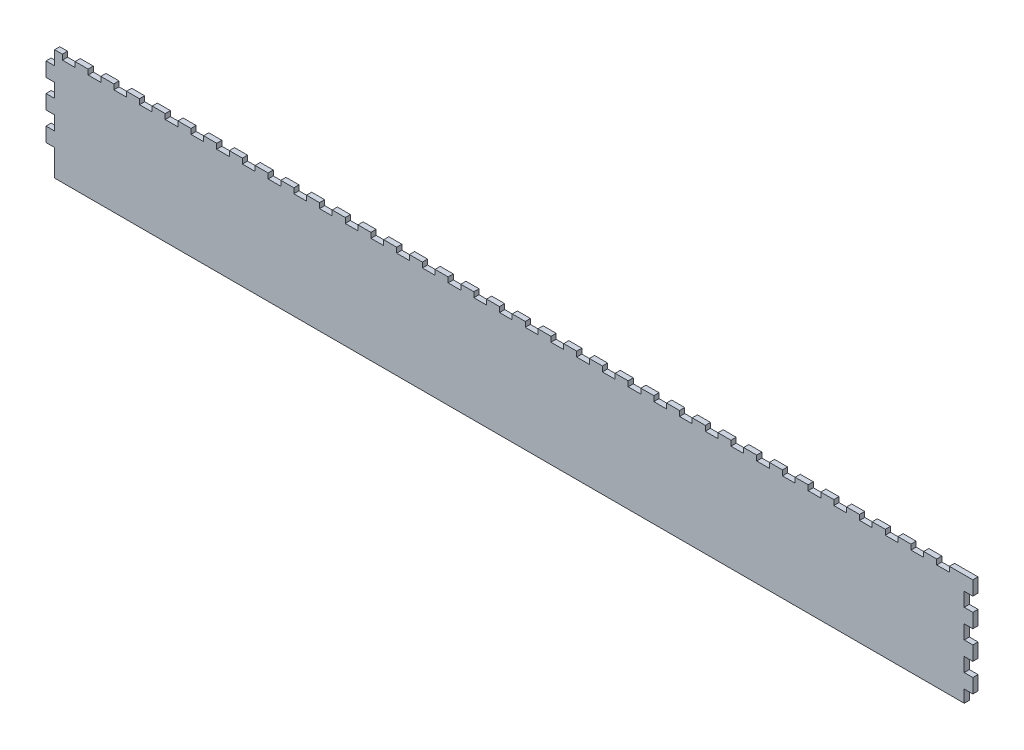
SolidWorks part; units mm, degrees
material "Perspex (TM) GS Acrylic Cast Sheet"
ref_plane "Front Plane" through (0, 0, 0) normal (0, 0, 1) x (1, 0, 0)
ref_plane "Top Plane" through (0, 0, 0) normal (0, 1, 0) x (1, 0, 0)
ref_plane "Right Plane" through (0, 0, 0) normal (1, 0, 0) x (0, 0, -1)
sketch "Sketch1" plane through (0, 0, 0) normal (0, 0, 1) x (1, 0, 0)
  line L0 (4.9997, 15.394) -> (4.9997, 0)
  line L1 (538.2002, 64.5533) -> (538.2002, -2.9072) construction
  line L1158 (538.3599, 64.6) -> (524.7414, 64.6)
  line L1159 (524.7414, 61.6) -> (524.7414, 64.6)
  line L1160 (524.7414, 61.6) -> (517.3729, 61.6)
  line L1161 (517.3729, 61.6) -> (517.3729, 64.6)
  line L1162 (517.3729, 64.6) -> (509.8045, 64.6)
  line L1163 (509.8045, 61.6) -> (509.8045, 64.6)
  line L1164 (509.8045, 61.6) -> (502.436, 61.6)
  line L1165 (502.436, 61.6) -> (502.436, 64.6)
  line L1166 (502.436, 64.6) -> (494.8676, 64.6)
  line L1167 (494.8676, 61.6) -> (494.8676, 64.6)
  line L1168 (494.8676, 61.6) -> (487.4991, 61.6)
  line L1169 (487.4991, 61.6) -> (487.4991, 64.6)
  line L1170 (487.4991, 64.6) -> (479.9307, 64.6)
  line L1171 (479.9307, 61.6) -> (479.9307, 64.6)
  line L1172 (479.9307, 61.6) -> (472.5622, 61.6)
  line L1173 (472.5622, 61.6) -> (472.5622, 64.6)
  line L1174 (472.5622, 64.6) -> (464.9938, 64.6)
  line L1175 (464.9938, 61.6) -> (464.9938, 64.6)
  line L1176 (464.9938, 61.6) -> (457.6253, 61.6)
  line L1177 (457.6253, 61.6) -> (457.6253, 64.6)
  line L1178 (457.6253, 64.6) -> (450.0567, 64.6)
  line L1179 (450.0567, 61.6) -> (450.0567, 64.6)
  line L1180 (450.0567, 61.6) -> (442.6886, 61.6)
  line L1181 (442.6886, 61.6) -> (442.6886, 64.6)
  line L1182 (442.6886, 64.6) -> (435.1201, 64.6)
  line L1183 (435.1201, 61.6) -> (435.1201, 64.6)
  line L1184 (435.1201, 61.6) -> (427.7516, 61.6)
  line L1185 (427.7516, 61.6) -> (427.7516, 64.6)
  line L1186 (427.7516, 64.6) -> (420.1831, 64.6)
  line L1187 (420.1831, 61.6) -> (420.1831, 64.6)
  line L1188 (420.1831, 61.6) -> (412.8147, 61.6)
  line L1189 (412.8147, 61.6) -> (412.8147, 64.6)
  line L1190 (412.8147, 64.6) -> (405.2462, 64.6)
  line L1191 (405.2462, 61.6) -> (405.2462, 64.6)
  line L1192 (405.2462, 61.6) -> (397.8777, 61.6)
  line L1193 (397.8777, 61.6) -> (397.8777, 64.6)
  line L1194 (397.8777, 64.6) -> (390.3092, 64.6)
  line L1195 (390.3092, 61.6) -> (390.3092, 64.6)
  line L1196 (390.3092, 61.6) -> (382.9407, 61.6)
  line L1197 (382.9407, 61.6) -> (382.9407, 64.6)
  line L1198 (382.9407, 64.6) -> (375.3722, 64.6)
  line L1199 (375.3722, 61.6) -> (375.3722, 64.6)
  line L1200 (375.3722, 61.6) -> (368.0038, 61.6)
  line L1201 (368.0038, 61.6) -> (368.0038, 64.6)
  line L1202 (368.0038, 64.6) -> (360.4356, 64.6)
  line L1203 (360.4356, 61.6) -> (360.4356, 64.6)
  line L1204 (360.4356, 61.6) -> (353.0672, 61.6)
  line L1205 (353.0672, 61.6) -> (353.0672, 64.6)
  line L1206 (353.0672, 64.6) -> (345.4986, 64.6)
  line L1207 (345.4986, 61.6) -> (345.4986, 64.6)
  line L1208 (345.4986, 61.6) -> (338.1302, 61.6)
  line L1209 (338.1302, 61.6) -> (338.1302, 64.6)
  line L1210 (338.1302, 64.6) -> (330.5617, 64.6)
  line L1211 (330.5617, 61.6) -> (330.5617, 64.6)
  line L1212 (330.5617, 61.6) -> (323.1932, 61.6)
  line L1213 (323.1932, 61.6) -> (323.1932, 64.6)
  line L1214 (323.1932, 64.6) -> (315.6247, 64.6)
  line L1215 (315.6247, 61.6) -> (315.6247, 64.6)
  line L1216 (315.6247, 61.6) -> (308.2563, 61.6)
  line L1217 (308.2563, 61.6) -> (308.2563, 64.6)
  line L1218 (308.2563, 64.6) -> (300.6878, 64.6)
  line L1219 (300.6878, 61.6) -> (300.6878, 64.6)
  line L1220 (300.6878, 61.6) -> (293.3193, 61.6)
  line L1221 (293.3193, 61.6) -> (293.3193, 64.6)
  line L1222 (293.3193, 64.6) -> (285.7508, 64.6)
  line L1223 (285.7508, 61.6) -> (285.7508, 64.6)
  line L1224 (285.7508, 61.6) -> (278.3823, 61.6)
  line L1225 (278.3823, 61.6) -> (278.3823, 64.6)
  line L1226 (278.3823, 64.6) -> (270.8142, 64.6)
  line L1227 (270.8142, 61.6) -> (270.8142, 64.6)
  line L1228 (270.8142, 61.6) -> (263.4457, 61.6)
  line L1229 (263.4457, 61.6) -> (263.4457, 64.6)
  line L1230 (263.4457, 64.6) -> (255.8772, 64.6)
  line L1231 (255.8772, 61.6) -> (255.8772, 64.6)
  line L1232 (255.8772, 61.6) -> (248.5088, 61.6)
  line L1233 (248.5088, 61.6) -> (248.5087, 64.6)
  line L1234 (248.5087, 64.6) -> (240.9403, 64.6)
  line L1235 (240.9403, 61.6) -> (240.9403, 64.6)
  line L1236 (240.9403, 61.6) -> (233.5718, 61.6)
  line L1237 (233.5718, 61.6) -> (233.5718, 64.6)
  line L1238 (233.5718, 64.6) -> (226.0033, 64.6)
  line L1239 (226.0033, 61.6) -> (226.0033, 64.6)
  line L1240 (226.0033, 61.6) -> (218.6348, 61.6)
  line L1241 (218.6348, 61.6) -> (218.6348, 64.6)
  line L1242 (218.6348, 64.6) -> (211.0664, 64.6)
  line L1243 (211.0664, 61.6) -> (211.0664, 64.6)
  line L1244 (211.0664, 61.6) -> (203.6979, 61.6)
  line L1245 (203.6979, 61.6) -> (203.6979, 64.6)
  line L1246 (203.6979, 64.6) -> (196.1297, 64.6)
  line L1247 (196.1297, 61.6) -> (196.1297, 64.6)
  line L1248 (196.1297, 61.6) -> (188.7613, 61.6)
  line L1249 (188.7613, 61.6) -> (188.7613, 64.6)
  line L1250 (188.7613, 64.6) -> (181.1928, 64.6)
  line L1251 (181.1928, 61.6) -> (181.1928, 64.6)
  line L1252 (181.1928, 61.6) -> (173.8243, 61.6)
  line L1253 (173.8243, 61.6) -> (173.8243, 64.6)
  line L1254 (173.8243, 64.6) -> (166.2558, 64.6)
  line L1255 (166.2558, 61.6) -> (166.2558, 64.6)
  line L1256 (166.2558, 61.6) -> (158.8873, 61.6)
  line L1257 (158.8873, 61.6) -> (158.8873, 64.6)
  line L1258 (158.8873, 64.6) -> (151.3188, 64.6)
  line L1259 (151.3188, 61.6) -> (151.3188, 64.6)
  line L1260 (151.3188, 61.6) -> (143.9504, 61.6)
  line L1261 (143.9504, 61.6) -> (143.9504, 64.6)
  line L1262 (143.9504, 64.6) -> (136.3819, 64.6)
  line L1263 (136.3819, 61.6) -> (136.3819, 64.6)
  line L1264 (136.3819, 61.6) -> (129.0134, 61.6)
  line L1265 (129.0134, 61.6) -> (129.0134, 64.6)
  line L1266 (129.0134, 64.6) -> (121.4449, 64.6)
  line L1267 (121.4449, 61.6) -> (121.4449, 64.6)
  line L1268 (121.4449, 61.6) -> (114.0764, 61.6)
  line L1269 (114.0764, 61.6) -> (114.0764, 64.6)
  line L1270 (114.0764, 64.6) -> (106.5083, 64.6)
  line L1271 (106.5083, 61.6) -> (106.5083, 64.6)
  line L1272 (106.5083, 61.6) -> (99.1398, 61.6)
  line L1273 (99.1398, 61.6) -> (99.1398, 64.6)
  line L1274 (99.1398, 64.6) -> (91.5713, 64.6)
  line L1275 (91.5713, 61.6) -> (91.5713, 64.6)
  line L1276 (91.5713, 61.6) -> (84.2029, 61.6)
  line L1277 (84.2029, 61.6) -> (84.2029, 64.6)
  line L1278 (84.2029, 64.6) -> (76.6344, 64.6)
  line L1279 (76.6344, 61.6) -> (76.6344, 64.6)
  line L1280 (76.6344, 61.6) -> (69.2659, 61.6)
  line L1281 (69.2659, 61.6) -> (69.2659, 64.6)
  line L1282 (69.2659, 64.6) -> (61.6974, 64.6)
  line L1283 (61.6974, 61.6) -> (61.6974, 64.6)
  line L1284 (61.6974, 61.6) -> (54.3289, 61.6)
  line L1285 (54.3289, 61.6) -> (54.3289, 64.6)
  line L1286 (54.3289, 64.6) -> (46.7604, 64.6)
  line L1287 (46.7604, 61.6) -> (46.7604, 64.6)
  line L1288 (46.7604, 61.6) -> (39.392, 61.6)
  line L1289 (39.392, 61.6) -> (39.392, 64.6)
  line L1290 (39.392, 64.6) -> (31.8235, 64.6)
  line L1291 (31.8235, 61.6) -> (31.8235, 64.6)
  line L1292 (31.8235, 61.6) -> (24.4554, 61.6)
  line L1293 (24.4554, 61.6) -> (24.4554, 64.6)
  line L1294 (24.4554, 64.6) -> (16.8869, 64.6)
  line L1295 (16.8869, 61.6) -> (16.8869, 64.6)
  line L1296 (16.8869, 61.6) -> (9.5184, 61.6)
  line L1297 (9.5184, 61.6) -> (9.5184, 64.6)
  line L1298 (9.5184, 64.6) -> (4.9997, 64.6)
  line L1299 (538.3599, 64.6) -> (538.3599, 56.3612)
  line L1300 (533.3598, 56.3612) -> (538.3599, 56.3612)
  line L1301 (533.3598, 56.3612) -> (533.3598, 48.2612)
  line L1302 (533.3598, 48.2612) -> (538.3599, 48.2612)
  line L1303 (538.3599, 48.2612) -> (538.3599, 39.9612)
  line L1304 (533.3598, 39.9612) -> (538.3599, 39.9612)
  line L1305 (533.3598, 39.9612) -> (533.3598, 31.8612)
  line L1306 (533.3598, 31.8612) -> (538.3599, 31.8612)
  line L1307 (538.3599, 31.8612) -> (538.3599, 23.5612)
  line L1308 (4.9997, 64.6) -> (4.9997, 56.4542)
  line L1309 (0, 56.4542) -> (4.9997, 56.4542)
  line L1310 (0, 56.4542) -> (0, 48.1649)
  line L1311 (0, 48.1649) -> (4.9997, 48.1649)
  line L1312 (4.9997, 48.1649) -> (4.9997, 40.0757)
  line L1313 (0, 40.0757) -> (4.9997, 40.0757)
  line L1314 (0, 40.0757) -> (0, 31.7864)
  line L1315 (0, 31.7864) -> (4.9997, 31.7864)
  line L1316 (4.9997, 31.7864) -> (4.9997, 23.6833)
  line L1317 (4.9997, 0) -> (533.3598, 0)
  line L1318 (533.3598, 23.5612) -> (538.3599, 23.5612)
  line L1319 (533.3598, 23.5612) -> (533.3598, 15.4612)
  line L1320 (533.3598, 15.4612) -> (538.3599, 15.4612)
  line L1321 (538.3599, 15.4612) -> (538.3599, 7.1612)
  line L1322 (533.3598, 7.1612) -> (538.3599, 7.1612)
  line L1323 (533.3598, 7.1612) -> (533.3598, 0)
  line L1324 (0, 23.6833) -> (4.9997, 23.6833)
  line L1325 (0, 23.6833) -> (0, 15.394)
  line L1326 (0, 15.394) -> (4.9997, 15.394)
  dimension "D1" = 64.6
  dimension "D2" = 64.6
  dimension "D4" = 8.1
  dimension "D5" = 8.3
  dimension "D6" = 8.3
  dimension "D7" = 8.3
extrude "Boss-Extrude1" add sketch "Sketch1" along normal blind 3
sketch "Sketch3" plane through (0, 0, 3) normal (0, 0, 1) x (1, 0, 0)
  line L0 (388.1696, 22.6554) -> (388.1696, 19.4364)
  line L1 (390.0144, 23.5966) -> (388.1696, 22.6554)
  line L2 (391.8592, 24.5377) -> (390.0144, 23.5966)
  line L3 (391.8592, 20.3776) -> (391.8592, 24.5377)
  line L4 (391.8592, 16.2174) -> (391.8592, 20.3776)
  line L5 (390.0144, 16.2174) -> (391.8592, 16.2174)
  line L6 (388.1696, 16.2174) -> (390.0144, 16.2174)
  line L7 (388.1696, 19.4364) -> (388.1696, 16.2174)
  line L8 (393.704, 27.2964) -> (393.704, 20.8345)
  line L9 (390.0144, 25.4413) -> (393.704, 27.2964)
  line L10 (386.3248, 23.5862) -> (390.0144, 25.4413)
  line L11 (386.3248, 18.9794) -> (386.3248, 23.5862)
  line L12 (386.3248, 14.3726) -> (386.3248, 18.9794)
  line L13 (390.0144, 14.3726) -> (386.3248, 14.3726)
  line L14 (393.704, 14.3726) -> (390.0144, 14.3726)
  line L15 (393.704, 20.8345) -> (393.704, 14.3726)
  line L16 (434.7504, 28.1897) -> (434.7504, 22.2036)
  line L17 (436.5952, 29.1309) -> (434.7504, 28.1897)
  line L18 (438.44, 30.072) -> (436.5952, 29.1309)
  line L19 (438.44, 23.1447) -> (438.44, 30.072)
  line L20 (438.44, 16.2174) -> (438.44, 23.1447)
  line L21 (436.5952, 16.2174) -> (438.44, 16.2174)
  line L22 (434.7504, 16.2174) -> (436.5952, 16.2174)
  line L23 (434.7504, 22.2036) -> (434.7504, 16.2174)
  line L24 (432.9056, 29.0475) -> (436.3429, 30.934)
  line L25 (432.9056, 21.7101) -> (432.9056, 29.0475)
  line L26 (432.9056, 14.3726) -> (432.9056, 21.7101)
  line L27 (436.5952, 14.3726) -> (432.9056, 14.3726)
  line L28 (440.2848, 14.3726) -> (436.5952, 14.3726)
  line L29 (440.2848, 23.5966) -> (440.2848, 14.3726)
  line L30 (146.503, 36.9712) -> (146.503, 26.5943)
  line L31 (148.3478, 36.9712) -> (146.503, 36.9712)
  line L32 (150.1926, 36.9712) -> (148.3478, 36.9712)
  line L33 (150.1926, 26.5943) -> (150.1926, 36.9712)
  line L34 (150.1926, 16.2174) -> (150.1926, 26.5943)
  line L35 (148.3478, 16.2174) -> (150.1926, 16.2174)
  line L36 (146.503, 16.2174) -> (148.3478, 16.2174)
  line L37 (146.503, 26.5943) -> (146.503, 16.2174)
  line L38 (152.0374, 38.816) -> (152.0374, 26.5943)
  line L39 (148.3478, 38.816) -> (152.0374, 38.816)
  line L40 (144.6582, 38.816) -> (148.3478, 38.816)
  line L41 (144.6582, 26.5943) -> (144.6582, 38.816)
  line L42 (144.6582, 14.3726) -> (144.6582, 26.5943)
  line L43 (148.3478, 14.3726) -> (144.6582, 14.3726)
  line L44 (152.0374, 14.3726) -> (148.3478, 14.3726)
  line L45 (152.0374, 26.5943) -> (152.0374, 14.3726)
  line L46 (186.6271, 36.9712) -> (186.6271, 26.5943)
  line L47 (188.4718, 36.9712) -> (186.6271, 36.9712)
  line L48 (190.3166, 36.9712) -> (188.4718, 36.9712)
  line L49 (190.3166, 26.5943) -> (190.3166, 36.9712)
  line L50 (190.3166, 16.2174) -> (190.3166, 26.5943)
  line L51 (188.4718, 16.2174) -> (190.3166, 16.2174)
  line L52 (186.6271, 16.2174) -> (188.4718, 16.2174)
  line L53 (186.6271, 26.5943) -> (186.6271, 16.2174)
  line L54 (192.1614, 38.816) -> (192.1614, 26.5943)
  line L55 (188.4718, 38.816) -> (192.1614, 38.816)
  line L56 (184.7823, 38.816) -> (188.4718, 38.816)
  line L57 (184.7823, 26.5943) -> (184.7823, 38.816)
  line L58 (184.7823, 14.3726) -> (184.7823, 26.5943)
  line L59 (188.4718, 14.3726) -> (184.7823, 14.3726)
  line L60 (192.1614, 14.3726) -> (188.4718, 14.3726)
  line L61 (192.1614, 26.5943) -> (192.1614, 14.3726)
  line L62 (393.704, 38.816) -> (393.704, 35.1213)
  line L63 (390.0144, 38.816) -> (393.704, 38.816)
  line L64 (386.3248, 38.816) -> (390.0144, 38.816)
  line L65 (386.3248, 36.9764) -> (386.3248, 38.816)
  line L66 (393.704, 31.4266) -> (390.0144, 33.2817)
  line L67 (393.704, 35.1213) -> (393.704, 31.4266)
  line L68 (307.6212, 47.3012) -> (307.6214, 47.3012)
  line L69 (305.9931, 14.3726) -> (306.1502, 32.1059)
  line L70 (308.802, 14.3726) -> (305.9931, 14.3726)
  line L71 (311.611, 14.3726) -> (308.802, 14.3726)
  line L72 (311.611, 12.5279) -> (311.611, 14.3726)
  line L73 (311.611, 10.683) -> (311.611, 12.5279)
  line L74 (304.2319, 10.683) -> (311.611, 10.683)
  line L75 (296.8527, 10.683) -> (304.2319, 10.683)
  line L76 (296.8527, 12.5279) -> (296.8527, 10.683)
  line L77 (296.8527, 14.3726) -> (296.8527, 12.5279)
  line L78 (299.6653, 14.3726) -> (296.8527, 14.3726)
  line L79 (302.478, 14.3726) -> (299.6653, 14.3726)
  line L80 (302.3172, 32.1058) -> (302.478, 14.3726)
  line L81 (300.5424, 16.2174) -> (300.5455, 30.3992)
  line L82 (297.7752, 16.2174) -> (300.5424, 16.2174)
  line L83 (295.0081, 16.2174) -> (297.7752, 16.2174)
  line L84 (295.0081, 12.5279) -> (295.0081, 16.2174)
  line L85 (295.0081, 8.8383) -> (295.0081, 12.5279)
  line L86 (304.232, 8.8383) -> (295.0081, 8.8383)
  line L87 (313.4559, 8.8383) -> (304.232, 8.8383)
  line L88 (313.4559, 12.5279) -> (313.4559, 8.8383)
  line L89 (313.4559, 16.2174) -> (313.4559, 12.5279)
  line L90 (310.6887, 16.2174) -> (313.4559, 16.2174)
  line L91 (307.9215, 16.2174) -> (310.6887, 16.2174)
  line L92 (307.9215, 29.9837) -> (307.9215, 16.2174)
  line L93 (434.8264, 41.7178) -> (436.4182, 40.9587)
  line L94 (434.5024, 46.0388) -> (434.8264, 41.7178)
  line L95 (440.2848, 36.9084) -> (436.5956, 38.8999)
  line L96 (440.2848, 40.3292) -> (440.2848, 36.9084)
  line L97 (443.8891, 10.683) -> (444.0767, 29.938)
  line L98 (436.5526, 10.683) -> (443.8891, 10.683)
  line L99 (429.2161, 10.683) -> (436.5526, 10.683)
  line L100 (429.2161, 21.1916) -> (429.2161, 10.683)
  line L101 (429.2161, 31.7001) -> (429.2161, 21.1916)
  line L102 (432.2682, 33.2052) -> (429.2161, 31.7001)
  line L103 (429.4466, 38.1242) -> (432.0696, 36.7311)
  line L104 (429.108, 43.1974) -> (429.4466, 38.1242)
  line L105 (427.3713, 37.155) -> (427.4169, 41.7904)
  line L106 (429.5604, 36.0915) -> (427.3713, 37.155)
  line L107 (431.7495, 35.0279) -> (429.5604, 36.0915)
  line L108 (429.5604, 33.9153) -> (431.7495, 35.0279)
  line L109 (427.3713, 32.8028) -> (429.5604, 33.9153)
  line L110 (427.3713, 20.8205) -> (427.3713, 32.8028)
  line L111 (427.3713, 8.8383) -> (427.3713, 20.8205)
  line L112 (436.5952, 8.8383) -> (427.3713, 8.8383)
  line L113 (445.8191, 8.8383) -> (436.5952, 8.8383)
  line L115 (445.8191, 26.5247) -> (445.8191, 8.8383)
  line L116 (209.3814, 48.2705) -> (209.3813, 48.2705)
  line L117 (213.607, 33.0511) -> (213.8934, 39.969)
  line L118 (211.6626, 38.816) -> (213.607, 33.0511)
  line L119 (226.29, 8.8383) -> (226.3356, 28.0932)
  line L120 (229.9795, 8.8383) -> (226.29, 8.8383)
  line L121 (233.6691, 8.8383) -> (229.9795, 8.8383)
  line L122 (233.6691, 20.1376) -> (233.6691, 8.8383)
  line L123 (233.6691, 31.4369) -> (233.6691, 20.1376)
  line L124 (235.5139, 31.4369) -> (233.6691, 31.4369)
  line L125 (237.3587, 31.4369) -> (235.5139, 31.4369)
  line L126 (237.3587, 20.1376) -> (237.3587, 31.4369)
  line L127 (237.3587, 8.8383) -> (237.3587, 20.1376)
  line L128 (241.0482, 8.8383) -> (237.3587, 8.8383)
  line L129 (244.7378, 8.8383) -> (241.0482, 8.8383)
  line L130 (244.735, 26.2484) -> (244.7378, 8.8383)
  line L131 (242.814, 10.683) -> (243.0138, 29.7074)
  line L132 (241.0087, 10.683) -> (242.814, 10.683)
  line L133 (239.2034, 10.683) -> (241.0087, 10.683)
  line L134 (239.2034, 21.9824) -> (239.2034, 10.683)
  line L135 (239.2034, 33.2817) -> (239.2034, 21.9824)
  line L136 (235.5138, 33.2817) -> (239.2034, 33.2817)
  line L137 (231.8242, 33.2817) -> (235.5138, 33.2817)
  line L138 (231.8242, 21.9824) -> (231.8242, 33.2817)
  line L139 (231.8242, 10.683) -> (231.8242, 21.9824)
  line L140 (230.0246, 10.683) -> (231.8242, 10.683)
  line L141 (228.225, 10.683) -> (230.0246, 10.683)
  line L142 (228.0101, 30.3992) -> (228.225, 10.683)
  line L143 (115.6029, 25.9025) -> (115.6485, 37.5477)
  line L144 (119.2925, 25.9025) -> (115.6029, 25.9025)
  line L145 (122.982, 25.9025) -> (119.2925, 25.9025)
  line L146 (122.982, 31.4369) -> (122.982, 25.9025)
  line L147 (122.982, 36.9712) -> (122.982, 31.4369)
  line L148 (124.8268, 36.9712) -> (122.982, 36.9712)
  line L149 (126.6716, 36.9712) -> (124.8268, 36.9712)
  line L150 (126.6716, 26.5943) -> (126.6716, 36.9712)
  line L151 (126.6716, 16.2174) -> (126.6716, 26.5943)
  line L152 (124.8268, 16.2174) -> (126.6716, 16.2174)
  line L153 (122.982, 16.2174) -> (124.8268, 16.2174)
  line L154 (122.982, 18.9846) -> (122.982, 16.2174)
  line L155 (122.982, 21.7517) -> (122.982, 18.9846)
  line L156 (119.2925, 21.7517) -> (122.982, 21.7517)
  line L157 (115.6029, 21.7517) -> (119.2925, 21.7517)
  line L158 (115.6029, 15.295) -> (115.6029, 21.7517)
  line L159 (115.6029, 8.8383) -> (115.6029, 15.295)
  line L160 (124.8268, 8.8383) -> (115.6029, 8.8383)
  line L161 (134.0507, 8.8383) -> (124.8268, 8.8383)
  line L162 (134.0507, 26.0635) -> (134.0507, 8.8383)
  line L163 (132.1262, 10.683) -> (132.3074, 29.4768)
  line L164 (124.787, 10.683) -> (132.1262, 10.683)
  line L165 (117.4477, 10.683) -> (124.787, 10.683)
  line L166 (117.4477, 15.295) -> (117.4477, 10.683)
  line L167 (117.4477, 19.907) -> (117.4477, 15.295)
  line L168 (119.2925, 19.907) -> (117.4477, 19.907)
  line L169 (121.1373, 19.907) -> (119.2925, 19.907)
  line L170 (121.1373, 17.1398) -> (121.1373, 19.907)
  line L171 (121.1373, 14.3726) -> (121.1373, 17.1398)
  line L172 (124.8268, 14.3726) -> (121.1373, 14.3726)
  line L173 (128.5164, 14.3726) -> (124.8268, 14.3726)
  line L174 (128.5164, 26.5943) -> (128.5164, 14.3726)
  line L175 (128.5164, 38.816) -> (128.5164, 26.5943)
  line L176 (124.8268, 38.816) -> (128.5164, 38.816)
  line L177 (121.1373, 38.816) -> (124.8268, 38.816)
  line L178 (121.1373, 33.2817) -> (121.1373, 38.816)
  line L179 (121.1373, 27.7473) -> (121.1373, 33.2817)
  line L180 (119.3512, 27.7473) -> (121.1373, 27.7473)
  line L181 (117.565, 27.7473) -> (119.3512, 27.7473)
  line L182 (117.3014, 39.6231) -> (117.565, 27.7473)
  line L183 (173.8694, 51.0505) -> (173.8695, 51.0505)
  line L184 (172.2496, 10.683) -> (172.4314, 31.5522)
  line L185 (170.445, 10.683) -> (172.2496, 10.683)
  line L186 (168.6403, 10.683) -> (170.445, 10.683)
  line L187 (168.6403, 24.7495) -> (168.6403, 10.683)
  line L188 (168.6403, 38.816) -> (168.6403, 24.7495)
  line L189 (165.9388, 38.816) -> (168.6403, 38.816)
  line L190 (163.2372, 38.816) -> (165.9388, 38.816)
  line L191 (162.9119, 44.0045) -> (163.2372, 38.816)
  line L192 (161.2613, 36.9712) -> (161.2644, 40.3149)
  line L193 (164.0285, 36.9712) -> (161.2613, 36.9712)
  line L194 (166.7956, 36.9712) -> (164.0285, 36.9712)
  line L195 (166.7956, 22.9047) -> (166.7956, 36.9712)
  line L196 (166.7956, 8.8383) -> (166.7956, 22.9047)
  line L197 (170.4852, 8.8383) -> (166.7956, 8.8383)
  line L198 (174.1748, 8.8383) -> (170.4852, 8.8383)
  line L199 (174.1748, 28.1389) -> (174.1748, 8.8383)
  line L200 (249.3497, 31.4369) -> (249.3953, 40.5455)
  line L201 (253.0393, 31.4369) -> (249.3497, 31.4369)
  line L202 (256.7288, 31.4369) -> (253.0393, 31.4369)
  line L203 (256.7288, 34.204) -> (256.7288, 31.4369)
  line L204 (256.7288, 36.9712) -> (256.7288, 34.204)
  line L205 (258.5736, 36.9712) -> (256.7288, 36.9712)
  line L206 (260.4184, 36.9712) -> (258.5736, 36.9712)
  line L207 (260.4184, 26.5943) -> (260.4184, 36.9712)
  line L208 (260.4184, 16.2174) -> (260.4184, 26.5943)
  line L209 (258.5736, 16.2174) -> (260.4184, 16.2174)
  line L210 (256.7288, 16.2174) -> (258.5736, 16.2174)
  line L211 (256.7288, 18.9846) -> (256.7288, 16.2174)
  line L212 (256.7288, 21.7517) -> (256.7288, 18.9846)
  line L213 (253.0393, 21.7517) -> (256.7288, 21.7517)
  line L214 (249.3497, 21.7517) -> (253.0393, 21.7517)
  line L215 (249.3497, 15.295) -> (249.3497, 21.7517)
  line L216 (249.3497, 8.8383) -> (249.3497, 15.295)
  line L217 (258.5736, 8.8383) -> (249.3497, 8.8383)
  line L218 (267.7975, 8.8383) -> (258.5736, 8.8383)
  line L219 (267.7975, 26.2941) -> (267.7975, 8.8383)
  line L220 (265.8667, 10.683) -> (266.0553, 29.7074)
  line L221 (258.5306, 10.683) -> (265.8667, 10.683)
  line L222 (251.1945, 10.683) -> (258.5306, 10.683)
  line L223 (251.1945, 15.295) -> (251.1945, 10.683)
  line L224 (251.1945, 19.907) -> (251.1945, 15.295)
  line L225 (253.0393, 19.907) -> (251.1945, 19.907)
  line L226 (254.884, 19.907) -> (253.0393, 19.907)
  line L227 (254.884, 17.1398) -> (254.884, 19.907)
  line L228 (254.884, 14.3726) -> (254.884, 17.1398)
  line L229 (258.5736, 14.3726) -> (254.884, 14.3726)
  line L230 (262.2632, 14.3726) -> (258.5736, 14.3726)
  line L231 (262.2632, 26.5943) -> (262.2632, 14.3726)
  line L232 (262.2632, 38.816) -> (262.2632, 26.5943)
  line L233 (258.5736, 38.816) -> (262.2632, 38.816)
  line L234 (254.884, 38.816) -> (258.5736, 38.816)
  line L235 (254.884, 36.0488) -> (254.884, 38.816)
  line L236 (254.884, 33.2817) -> (254.884, 36.0488)
  line L237 (253.1053, 33.2817) -> (254.884, 33.2817)
  line L238 (251.3265, 33.2817) -> (253.1053, 33.2817)
  line L239 (251.0415, 42.6209) -> (251.3265, 33.2817)
  line L240 (352.3522, 51.0505) -> (352.3523, 51.0505)
  line L241 (350.7324, 10.683) -> (350.9142, 31.5522)
  line L242 (348.9277, 10.683) -> (350.7324, 10.683)
  line L243 (347.1231, 10.683) -> (348.9277, 10.683)
  line L244 (347.1231, 24.7495) -> (347.1231, 10.683)
  line L245 (347.1231, 38.816) -> (347.1231, 24.7495)
  line L246 (344.4215, 38.816) -> (347.1231, 38.816)
  line L247 (341.72, 38.816) -> (344.4215, 38.816)
  line L248 (341.3947, 44.0045) -> (341.72, 38.816)
  line L249 (339.7441, 36.9712) -> (339.7472, 40.3149)
  line L250 (342.5112, 36.9712) -> (339.7441, 36.9712)
  line L251 (345.2784, 36.9712) -> (342.5112, 36.9712)
  line L252 (345.2784, 22.9047) -> (345.2784, 36.9712)
  line L253 (345.2784, 8.8383) -> (345.2784, 22.9047)
  line L254 (348.968, 8.8383) -> (345.2784, 8.8383)
  line L255 (352.6576, 8.8383) -> (348.968, 8.8383)
  line L256 (352.6576, 28.1389) -> (352.6576, 8.8383)
  line L257 (397.3133, 10.683) -> (397.4951, 31.5522)
  line L258 (389.9743, 10.683) -> (397.3133, 10.683)
  line L259 (382.6353, 10.683) -> (389.9743, 10.683)
  line L260 (382.6353, 18.4244) -> (382.6353, 10.683)
  line L261 (382.6353, 26.1657) -> (382.6353, 18.4244)
  line L262 (385.6874, 27.6708) -> (382.6353, 26.1657)
  line L263 (382.8659, 32.5898) -> (385.4889, 31.1967)
  line L264 (382.5801, 40.208) -> (382.8659, 32.5898)
  line L265 (380.7905, 31.6207) -> (380.8361, 38.7926)
  line L266 (382.9665, 30.5635) -> (380.7905, 31.6207)
  line L267 (385.1425, 29.5063) -> (382.9665, 30.5635)
  line L268 (383.3124, 28.3986) -> (385.1425, 29.5063)
  line L269 (380.7905, 8.8383) -> (380.7905, 18.0622)
  line L270 (390.0144, 8.8383) -> (380.7905, 8.8383)
  line L271 (399.2383, 8.8383) -> (390.0144, 8.8383)
  line L272 (399.2383, 28.1389) -> (399.2383, 8.8383)
  line L273 (272.4095, 36.9712) -> (272.4551, 43.5433)
  line L274 (277.9438, 36.9712) -> (272.4095, 36.9712)
  line L275 (283.4782, 36.9712) -> (277.9438, 36.9712)
  line L276 (283.4782, 35.1264) -> (283.4782, 36.9712)
  line L277 (283.4782, 33.2817) -> (283.4782, 35.1264)
  line L278 (277.9438, 33.2817) -> (283.4782, 33.2817)
  line L279 (272.4095, 33.2817) -> (277.9438, 33.2817)
  line L280 (272.4095, 29.5921) -> (272.4095, 33.2817)
  line L281 (272.4095, 25.9025) -> (272.4095, 29.5921)
  line L282 (277.9438, 25.9025) -> (272.4095, 25.9025)
  line L283 (283.4782, 25.9025) -> (277.9438, 25.9025)
  line L284 (283.4782, 21.06) -> (283.4782, 25.9025)
  line L285 (283.4782, 16.2174) -> (283.4782, 21.06)
  line L286 (281.6334, 16.2174) -> (283.4782, 16.2174)
  line L287 (279.7886, 16.2174) -> (281.6334, 16.2174)
  line L288 (279.7886, 18.9846) -> (279.7886, 16.2174)
  line L289 (279.7886, 21.7517) -> (279.7886, 18.9846)
  line L290 (276.099, 21.7517) -> (279.7886, 21.7517)
  line L291 (272.4095, 21.7517) -> (276.099, 21.7517)
  line L292 (272.4095, 15.295) -> (272.4095, 21.7517)
  line L293 (272.4095, 8.8383) -> (272.4095, 15.295)
  line L294 (281.6334, 8.8383) -> (272.4095, 8.8383)
  line L295 (290.8573, 8.8383) -> (281.6334, 8.8383)
  line L296 (290.8573, 26.9859) -> (290.8573, 8.8383)
  line L297 (288.9288, 10.683) -> (289.1147, 30.3992)
  line L298 (281.5915, 10.683) -> (288.9288, 10.683)
  line L299 (274.2543, 10.683) -> (281.5915, 10.683)
  line L300 (274.2543, 15.295) -> (274.2543, 10.683)
  line L301 (274.2543, 19.907) -> (274.2543, 15.295)
  line L302 (276.099, 19.907) -> (274.2543, 19.907)
  line L303 (277.9438, 19.907) -> (276.099, 19.907)
  line L304 (277.9438, 17.1398) -> (277.9438, 19.907)
  line L305 (277.9438, 14.3726) -> (277.9438, 17.1398)
  line L306 (281.6334, 14.3726) -> (277.9438, 14.3726)
  line L307 (285.323, 14.3726) -> (281.6334, 14.3726)
  line L308 (285.323, 21.06) -> (285.323, 14.3726)
  line L309 (285.323, 27.7473) -> (285.323, 21.06)
  line L310 (279.7886, 27.7473) -> (285.323, 27.7473)
  line L311 (274.2543, 27.7473) -> (279.7886, 27.7473)
  line L312 (274.2543, 29.5921) -> (274.2543, 27.7473)
  line L313 (274.2543, 31.4369) -> (274.2543, 29.5921)
  line L314 (279.7886, 31.4369) -> (274.2543, 31.4369)
  line L315 (285.323, 31.4369) -> (279.7886, 31.4369)
  line L316 (285.323, 35.1264) -> (285.323, 31.4369)
  line L317 (285.323, 38.816) -> (285.323, 35.1264)
  line L318 (279.8603, 38.816) -> (285.323, 38.816)
  line L319 (274.3977, 38.816) -> (279.8603, 38.816)
  line L320 (274.0865, 45.6186) -> (274.3977, 38.816)
  line L321 (357.2695, 36.9712) -> (357.3151, 43.5433)
  line L322 (362.8039, 36.9712) -> (357.2695, 36.9712)
  line L323 (368.3382, 36.9712) -> (362.8039, 36.9712)
  line L324 (368.3382, 35.1264) -> (368.3382, 36.9712)
  line L325 (368.3382, 33.2817) -> (368.3382, 35.1264)
  line L326 (362.8039, 33.2817) -> (368.3382, 33.2817)
  line L327 (357.2695, 33.2817) -> (362.8039, 33.2817)
  line L328 (357.2695, 29.5921) -> (357.2695, 33.2817)
  line L329 (357.2695, 25.9025) -> (357.2695, 29.5921)
  line L330 (362.8039, 25.9025) -> (357.2695, 25.9025)
  line L331 (368.3382, 25.9025) -> (362.8039, 25.9025)
  line L332 (368.3382, 21.06) -> (368.3382, 25.9025)
  line L333 (368.3382, 16.2174) -> (368.3382, 21.06)
  line L334 (366.4934, 16.2174) -> (368.3382, 16.2174)
  line L335 (364.6486, 16.2174) -> (366.4934, 16.2174)
  line L336 (364.6486, 18.9846) -> (364.6486, 16.2174)
  line L337 (364.6486, 21.7517) -> (364.6486, 18.9846)
  line L338 (360.9591, 21.7517) -> (364.6486, 21.7517)
  line L339 (357.2695, 21.7517) -> (360.9591, 21.7517)
  line L340 (357.2695, 15.295) -> (357.2695, 21.7517)
  line L341 (357.2695, 8.8383) -> (357.2695, 15.295)
  line L342 (366.4934, 8.8383) -> (357.2695, 8.8383)
  line L343 (375.7173, 8.8383) -> (366.4934, 8.8383)
  line L344 (375.7173, 26.9859) -> (375.7173, 8.8383)
  line L345 (373.7888, 10.683) -> (373.9747, 30.3992)
  line L346 (366.4515, 10.683) -> (373.7888, 10.683)
  line L347 (359.1143, 10.683) -> (366.4515, 10.683)
  line L348 (359.1143, 15.295) -> (359.1143, 10.683)
  line L349 (359.1143, 19.907) -> (359.1143, 15.295)
  line L350 (360.9591, 19.907) -> (359.1143, 19.907)
  line L351 (362.8039, 19.907) -> (360.9591, 19.907)
  line L352 (362.8039, 17.1398) -> (362.8039, 19.907)
  line L353 (362.8039, 14.3726) -> (362.8039, 17.1398)
  line L354 (366.4934, 14.3726) -> (362.8039, 14.3726)
  line L355 (370.183, 14.3726) -> (366.4934, 14.3726)
  line L356 (370.183, 21.06) -> (370.183, 14.3726)
  line L357 (370.183, 27.7473) -> (370.183, 21.06)
  line L358 (364.6486, 27.7473) -> (370.183, 27.7473)
  line L359 (359.1143, 27.7473) -> (364.6486, 27.7473)
  line L360 (359.1143, 29.5921) -> (359.1143, 27.7473)
  line L361 (359.1143, 31.4369) -> (359.1143, 29.5921)
  line L362 (364.6486, 31.4369) -> (359.1143, 31.4369)
  line L363 (370.183, 31.4369) -> (364.6486, 31.4369)
  line L364 (370.183, 35.1264) -> (370.183, 31.4369)
  line L365 (370.183, 38.816) -> (370.183, 35.1264)
  line L366 (364.7204, 38.816) -> (370.183, 38.816)
  line L367 (359.2577, 38.816) -> (364.7204, 38.816)
  line L368 (358.9465, 45.6186) -> (359.2577, 38.816)
  line L369 (403.8503, 36.9712) -> (403.8959, 43.5433)
  line L370 (409.3846, 36.9712) -> (403.8503, 36.9712)
  line L371 (414.919, 36.9712) -> (409.3846, 36.9712)
  line L372 (414.919, 35.1264) -> (414.919, 36.9712)
  line L373 (414.919, 33.2817) -> (414.919, 35.1264)
  line L374 (409.3846, 33.2817) -> (414.919, 33.2817)
  line L375 (403.8503, 33.2817) -> (409.3846, 33.2817)
  line L376 (403.8503, 29.5921) -> (403.8503, 33.2817)
  line L377 (403.8503, 25.9025) -> (403.8503, 29.5921)
  line L378 (409.3846, 25.9025) -> (403.8503, 25.9025)
  line L379 (414.919, 25.9025) -> (409.3846, 25.9025)
  line L380 (414.919, 21.06) -> (414.919, 25.9025)
  line L381 (414.919, 16.2174) -> (414.919, 21.06)
  line L382 (413.0742, 16.2174) -> (414.919, 16.2174)
  line L383 (411.2294, 16.2174) -> (413.0742, 16.2174)
  line L384 (411.2294, 18.9846) -> (411.2294, 16.2174)
  line L385 (411.2294, 21.7517) -> (411.2294, 18.9846)
  line L386 (407.5398, 21.7517) -> (411.2294, 21.7517)
  line L387 (403.8503, 21.7517) -> (407.5398, 21.7517)
  line L388 (403.8503, 15.295) -> (403.8503, 21.7517)
  line L389 (403.8503, 8.8383) -> (403.8503, 15.295)
  line L390 (413.0742, 8.8383) -> (403.8503, 8.8383)
  line L391 (422.2981, 8.8383) -> (413.0742, 8.8383)
  line L393 (422.2981, 26.9859) -> (422.2981, 8.8383)
  line L394 (420.3695, 10.683) -> (420.5554, 30.3992)
  line L395 (413.0323, 10.683) -> (420.3695, 10.683)
  line L396 (405.6951, 10.683) -> (413.0323, 10.683)
  line L397 (405.6951, 15.295) -> (405.6951, 10.683)
  line L398 (405.6951, 19.907) -> (405.6951, 15.295)
  line L399 (407.5398, 19.907) -> (405.6951, 19.907)
  line L400 (409.3846, 19.907) -> (407.5398, 19.907)
  line L401 (409.3846, 17.1398) -> (409.3846, 19.907)
  line L402 (409.3846, 14.3726) -> (409.3846, 17.1398)
  line L403 (413.0742, 14.3726) -> (409.3846, 14.3726)
  line L404 (416.7638, 14.3726) -> (413.0742, 14.3726)
  line L405 (416.7638, 21.06) -> (416.7638, 14.3726)
  line L406 (416.7638, 27.7473) -> (416.7638, 21.06)
  line L407 (411.2294, 27.7473) -> (416.7638, 27.7473)
  line L408 (405.6951, 27.7473) -> (411.2294, 27.7473)
  line L409 (405.6951, 29.5921) -> (405.6951, 27.7473)
  line L410 (405.6951, 31.4369) -> (405.6951, 29.5921)
  line L411 (411.2294, 31.4369) -> (405.6951, 31.4369)
  line L412 (416.7638, 31.4369) -> (411.2294, 31.4369)
  line L413 (416.7638, 35.1264) -> (416.7638, 31.4369)
  line L414 (416.7638, 38.816) -> (416.7638, 35.1264)
  line L415 (411.3011, 38.816) -> (416.7638, 38.816)
  line L416 (405.8385, 38.816) -> (411.3011, 38.816)
  line L417 (405.5273, 45.6186) -> (405.8385, 38.816)
  line L418 (157.2664, 52.4341) -> (157.2665, 52.4341)
  line L419 (155.6485, 10.683) -> (155.828, 32.244)
  line L420 (148.3516, 10.683) -> (155.6485, 10.683)
  line L421 (141.0546, 10.683) -> (148.3516, 10.683)
  line L422 (140.866, 29.7074) -> (141.0546, 10.683)
  line L423 (139.1239, 8.8383) -> (139.127, 26.7096)
  line L424 (148.3478, 8.8383) -> (139.1239, 8.8383)
  line L425 (157.5717, 8.8383) -> (148.3478, 8.8383)
  line L426 (157.5717, 28.8307) -> (157.5717, 8.8383)
  line L427 (197.3904, 52.4341) -> (197.3905, 52.4341)
  line L428 (195.7726, 10.683) -> (195.9521, 32.244)
  line L429 (188.4756, 10.683) -> (195.7726, 10.683)
  line L430 (181.1786, 10.683) -> (188.4756, 10.683)
  line L431 (180.9901, 29.7074) -> (181.1786, 10.683)
  line L432 (179.2479, 8.8383) -> (179.251, 26.7096)
  line L433 (188.4718, 8.8383) -> (179.2479, 8.8383)
  line L434 (197.6958, 8.8383) -> (188.4718, 8.8383)
  line L435 (197.6958, 28.8307) -> (197.6958, 8.8383)
  line L436 (238.9031, 52.3743) -> (238.9032, 52.3743)
  line L437 (237.2189, 38.816) -> (237.4814, 46.9413)
  line L438 (235.5032, 38.816) -> (237.2189, 38.816)
  line L439 (233.7876, 38.816) -> (235.5032, 38.816)
  line L440 (233.4589, 43.8858) -> (233.7876, 38.816)
  line L441 (231.8242, 36.9712) -> (231.8274, 40.0843)
  line L442 (235.5138, 36.9712) -> (231.8242, 36.9712)
  line L443 (239.2034, 36.9712) -> (235.5138, 36.9712)
  line L444 (239.2034, 42.8972) -> (239.2034, 36.9712)
  line L445 (220.9063, 52.9282) -> (220.9065, 52.9282)
  line L446 (219.3002, 10.683) -> (219.4918, 32.244)
  line L447 (217.333, 10.683) -> (219.3002, 10.683)
  line L448 (215.3659, 10.683) -> (217.333, 10.683)
  line L449 (211.9498, 20.6957) -> (215.3659, 10.683)
  line L450 (208.5337, 30.7084) -> (211.9498, 20.6957)
  line L451 (208.4094, 20.6957) -> (208.5337, 30.7084)
  line L452 (208.2851, 10.683) -> (208.4094, 20.6957)
  line L453 (206.4912, 10.683) -> (208.2851, 10.683)
  line L454 (204.6973, 10.683) -> (206.4912, 10.683)
  line L455 (204.492, 30.3992) -> (204.6973, 10.683)
  line L456 (202.7689, 8.8383) -> (202.772, 27.632)
  line L457 (206.4585, 8.8383) -> (202.7689, 8.8383)
  line L458 (210.148, 8.8383) -> (206.4585, 8.8383)
  line L459 (210.1795, 14.4879) -> (210.148, 8.8383)
  line L460 (210.2109, 20.1376) -> (210.1795, 14.4879)
  line L461 (212.1395, 14.6032) -> (210.2109, 20.1376)
  line L462 (214.0682, 9.0689) -> (212.1395, 14.6032)
  line L463 (217.6425, 8.9342) -> (214.0682, 9.0689)
  line L464 (221.2167, 8.7995) -> (217.6425, 8.9342)
  line L465 (221.2167, 29.0419) -> (221.2167, 8.7995)
  line L466 (110.6808, 53.3894) -> (110.6806, 53.3894)
  line L467 (109.0112, 38.816) -> (109.2853, 46.541)
  line L468 (103.5444, 38.816) -> (109.0112, 38.816)
  line L469 (98.0776, 38.816) -> (103.5444, 38.816)
  line L470 (98.0776, 35.1264) -> (98.0776, 38.816)
  line L471 (98.0776, 31.4369) -> (98.0776, 35.1264)
  line L472 (103.612, 31.4369) -> (98.0776, 31.4369)
  line L473 (109.1463, 31.4369) -> (103.612, 31.4369)
  line L474 (109.1463, 21.06) -> (109.1463, 31.4369)
  line L475 (109.1463, 10.683) -> (109.1463, 21.06)
  line L476 (107.3016, 10.683) -> (109.1463, 10.683)
  line L477 (105.4568, 10.683) -> (107.3016, 10.683)
  line L478 (105.4568, 19.2152) -> (105.4568, 10.683)
  line L479 (105.4568, 27.7473) -> (105.4568, 19.2152)
  line L480 (101.7672, 27.7473) -> (105.4568, 27.7473)
  line L481 (98.0776, 27.7473) -> (101.7672, 27.7473)
  line L482 (98.0776, 19.2152) -> (98.0776, 27.7473)
  line L483 (98.0776, 10.683) -> (98.0776, 19.2152)
  line L484 (96.2762, 10.683) -> (98.0776, 10.683)
  line L485 (94.4749, 10.683) -> (96.2762, 10.683)
  line L486 (94.2854, 29.4768) -> (94.4749, 10.683)
  line L487 (92.5431, 8.8383) -> (92.5465, 26.479)
  line L488 (96.2327, 8.8383) -> (92.5431, 8.8383)
  line L489 (99.9222, 8.8383) -> (96.2327, 8.8383)
  line L490 (99.9222, 17.3704) -> (99.9222, 8.8383)
  line L491 (99.9222, 25.9025) -> (99.9222, 17.3704)
  line L492 (101.767, 25.9025) -> (99.9222, 25.9025)
  line L493 (103.6118, 25.9025) -> (101.767, 25.9025)
  line L494 (103.6118, 17.3704) -> (103.6118, 25.9025)
  line L495 (103.6118, 8.8383) -> (103.6118, 17.3704)
  line L496 (107.3014, 8.8383) -> (103.6118, 8.8383)
  line L497 (110.9909, 8.8383) -> (107.3014, 8.8383)
  line L498 (110.9909, 21.06) -> (110.9909, 8.8383)
  line L499 (110.9909, 33.2817) -> (110.9909, 21.06)
  line L500 (105.4566, 33.2817) -> (110.9909, 33.2817)
  line L501 (99.9222, 33.2817) -> (105.4566, 33.2817)
  line L502 (99.9222, 35.1264) -> (99.9222, 33.2817)
  line L503 (99.9222, 36.9712) -> (99.9222, 35.1264)
  line L504 (105.4566, 36.9712) -> (99.9222, 36.9712)
  line L505 (110.9909, 36.9712) -> (105.4566, 36.9712)
  line L508 (110.9909, 43.3584) -> (110.9909, 36.9712)
  spline S0 degree 3 poles (440.0324, 32.8204) (440.1712, 32.8204) (440.2848, 28.6697) (440.2848, 23.5966) knots 0 0 0 0 1 1 1 1
  spline S1 degree 3 poles (436.3429, 30.934) (438.2333, 31.9716) (439.8937, 32.8204) (440.0324, 32.8204) knots 0 0 0 0 1 1 1 1
  spline S2 degree 3 poles (390.0144, 36.9712) (388.9998, 36.9712) (388.1696, 36.8021) (388.1696, 36.5954) knots 0 0 0 0 1 1 1 1
  spline S3 degree 3 poles (391.8592, 35.8182) (391.8592, 36.8559) (391.6747, 36.9712) (390.0144, 36.9712) knots 0 0 0 0 1 1 1 1
  spline S4 degree 3 poles (391.6442, 34.6652) (391.7625, 34.6652) (391.8592, 35.1841) (391.8592, 35.8182) knots 0 0 0 0 1 1 1 1
  spline S5 degree 3 poles (388.1696, 36.5954) (388.1696, 36.2689) (391.0564, 34.6652) (391.6442, 34.6652) knots 0 0 0 0 1 1 1 1
  spline S6 degree 3 poles (390.0144, 33.2817) (386.3291, 35.1346) (386.3248, 35.1389) (386.3248, 36.9764) knots 0 0 0 0 1 1 1 1
  spline S7 degree 3 poles (306.8141, 50.3458) (307.1825, 50.714) (307.4031, 49.8818) (307.6212, 47.3012) knots 0 0 0 0 1 1 1 1
  spline S8 degree 3 poles (306.1502, 32.1059) (306.2571, 44.1818) (306.4689, 50.0009) (306.8141, 50.3458) knots 0 0 0 0 1 1 1 1
  spline S9 degree 3 poles (301.6488, 50.3464) (301.9948, 50.0006) (302.2076, 44.1923) (302.3172, 32.1058) knots 0 0 0 0 1 1 1 1
  spline S10 degree 3 poles (300.5455, 30.3992) (300.5492, 46.0081) (300.8341, 51.1607) (301.6488, 50.3464) knots 0 0 0 0 1 1 1 1
  spline S11 degree 3 poles (307.6214, 47.3012) (307.7865, 45.348) (307.9215, 37.5551) (307.9215, 29.9837) knots 0 0 0 0 1 1 1 1
  spline S12 degree 3 poles (439.3147, 50.4827) (439.518, 50.686) (439.8195, 49.2544) (439.9846, 47.3012) knots 0 0 0 0 1 1 1 1
  spline S13 degree 3 poles (438.6246, 45.1563) (438.8008, 47.8825) (439.1114, 50.2794) (439.3147, 50.4827) knots 0 0 0 0 1 1 1 1
  spline S14 degree 3 poles (438.1571, 40.1996) (438.2379, 40.1996) (438.4483, 42.4301) (438.6246, 45.1563) knots 0 0 0 0 1 1 1 1
  spline S15 degree 3 poles (436.4182, 40.9587) (437.2937, 40.5412) (438.0762, 40.1996) (438.1571, 40.1996) knots 0 0 0 0 1 1 1 1
  spline S16 degree 3 poles (433.8381, 50.5702) (434.0253, 50.4546) (434.3242, 48.4154) (434.5024, 46.0388) knots 0 0 0 0 1 1 1 1
  spline S17 degree 3 poles (432.9094, 42.7362) (432.9142, 45.9695) (433.4856, 50.7881) (433.8381, 50.5702) knots 0 0 0 0 1 1 1 1
  spline S18 degree 3 poles (436.5956, 38.8999) (432.9295, 40.879) (432.9065, 40.9029) (432.9094, 42.7362) knots 0 0 0 0 1 1 1 1
  spline S19 degree 3 poles (439.9846, 47.3012) (440.1497, 45.348) (440.2848, 42.2106) (440.2848, 40.3292) knots 0 0 0 0 1 1 1 1
  spline S20 degree 3 poles (444.7365, 50.313) (445.1342, 51.2565) (445.2567, 50.8639) (445.5139, 47.8221) knots 0 0 0 0 1 1 1 1
  spline S21 degree 3 poles (444.0767, 29.938) (444.1902, 41.5889) (444.4508, 49.6352) (444.7365, 50.313) knots 0 0 0 0 1 1 1 1
  spline S22 degree 3 poles (435.0065, 35.0241) (435.1791, 34.8515) (433.9469, 34.033) (432.2682, 33.2052) knots 0 0 0 0 1 1 1 1
  spline S23 degree 3 poles (432.0696, 36.7311) (433.5123, 35.9648) (434.8339, 35.1967) (435.0065, 35.0241) knots 0 0 0 0 1 1 1 1
  spline S24 degree 3 poles (428.4445, 49.8847) (428.6232, 48.9969) (428.9218, 45.9876) (429.108, 43.1974) knots 0 0 0 0 1 1 1 1
  spline S25 degree 3 poles (427.791, 48.9623) (428.1116, 51.4371) (428.1275, 51.4595) (428.4445, 49.8847) knots 0 0 0 0 1 1 1 1
  spline S26 degree 3 poles (427.4169, 41.7904) (427.442, 44.3398) (427.6103, 47.5672) (427.791, 48.9623) knots 0 0 0 0 1 1 1 1
  spline S27 degree 3 poles (445.5139, 47.8221) (445.6817, 45.8361) (445.8191, 36.2523) (445.8191, 26.5247) knots 0 0 0 0 1 1 1 1
  spline S28 degree 3 poles (208.7094, 50.1153) (209.0166, 51.8066) (209.0725, 51.6532) (209.3814, 48.2705) knots 0 0 0 0 1 1 1 1
  spline S29 degree 3 poles (211.7882, 33.2817) (208.0436, 44.435) (207.8599, 45.4388) (208.7094, 50.1153) knots 0 0 0 0 1 1 1 1
  spline S30 degree 3 poles (215.6064, 23.5965) (215.4885, 22.8388) (214.1796, 26.1587) (211.7882, 33.2817) knots 0 0 0 0 1 1 1 1
  spline S31 degree 3 poles (215.5946, 36.8571) (215.6998, 30.1979) (215.7051, 24.2307) (215.6064, 23.5965) knots 0 0 0 0 1 1 1 1
  spline S32 degree 3 poles (214.8511, 49.5169) (215.2416, 49.1264) (215.4593, 45.4186) (215.5946, 36.8571) knots 0 0 0 0 1 1 1 1
  spline S33 degree 3 poles (214.2393, 48.4781) (214.2855, 49.7137) (214.4222, 49.9458) (214.8511, 49.5169) knots 0 0 0 0 1 1 1 1
  spline S34 degree 3 poles (213.8934, 39.969) (214.0509, 43.7739) (214.2065, 47.6029) (214.2393, 48.4781) knots 0 0 0 0 1 1 1 1
  spline S35 degree 3 poles (209.3813, 48.2705) (209.5981, 45.8957) (210.4111, 42.5266) (211.6626, 38.816) knots 0 0 0 0 1 1 1 1
  spline S36 degree 3 poles (226.3356, 28.0932) (226.3824, 47.8723) (226.6379, 53.4571) (227.3959, 51.2683) knots 0 0 0 0 1 1 1 1
  spline S37 degree 3 poles (243.6655, 50.1153) (244.4212, 52.4293) (244.7319, 45.4943) (244.735, 26.2484) knots 0 0 0 0 1 1 1 1
  spline S38 degree 3 poles (243.0138, 29.7074) (243.1247, 40.2662) (243.4147, 49.3474) (243.6655, 50.1153) knots 0 0 0 0 1 1 1 1
  spline S39 degree 3 poles (227.3959, 51.2683) (227.6154, 50.6341) (227.8918, 41.243) (228.0101, 30.3992) knots 0 0 0 0 1 1 1 1
  spline S40 degree 3 poles (116.0062, 51.7295) (116.2921, 54.0529) (116.3485, 54.1498) (116.6781, 52.8825) knots 0 0 0 0 1 1 1 1
  spline S41 degree 3 poles (115.6485, 37.5477) (115.6736, 43.9526) (115.8346, 50.3344) (116.0062, 51.7295) knots 0 0 0 0 1 1 1 1
  spline S42 degree 3 poles (132.9644, 49.3906) (133.7584, 51.2595) (134.0507, 44.9814) (134.0507, 26.0635) knots 0 0 0 0 1 1 1 1
  spline S43 degree 3 poles (132.3074, 29.4768) (132.4179, 40.934) (132.6744, 48.7078) (132.9644, 49.3906) knots 0 0 0 0 1 1 1 1
  spline S44 degree 3 poles (116.6781, 52.8825) (116.8759, 52.1215) (117.1564, 46.1548) (117.3014, 39.6231) knots 0 0 0 0 1 1 1 1
  spline S45 degree 3 poles (173.0887, 53.5414) (173.4904, 54.4876) (173.6115, 54.1009) (173.8694, 51.0505) knots 0 0 0 0 1 1 1 1
  spline S46 degree 3 poles (172.4314, 31.5522) (172.5436, 44.4268) (172.7954, 52.8504) (173.0887, 53.5414) knots 0 0 0 0 1 1 1 1
  spline S47 degree 3 poles (162.2233, 49.5622) (162.4232, 49.3591) (162.733, 46.8581) (162.9119, 44.0045) knots 0 0 0 0 1 1 1 1
  spline S48 degree 3 poles (161.2644, 40.3149) (161.2689, 44.9837) (161.7895, 50.0032) (162.2233, 49.5622) knots 0 0 0 0 1 1 1 1
  spline S49 degree 3 poles (173.8695, 51.0505) (174.0374, 49.0645) (174.1748, 38.7543) (174.1748, 28.1389) knots 0 0 0 0 1 1 1 1
  spline S50 degree 3 poles (249.753, 52.1907) (250.0364, 54.4936) (250.0969, 54.5998) (250.4108, 53.3437) knots 0 0 0 0 1 1 1 1
  spline S51 degree 3 poles (249.3953, 40.5455) (249.4204, 45.5552) (249.5814, 50.7955) (249.753, 52.1907) knots 0 0 0 0 1 1 1 1
  spline S52 degree 3 poles (266.7154, 49.8518) (267.5065, 51.7306) (267.7975, 45.3953) (267.7975, 26.2941) knots 0 0 0 0 1 1 1 1
  spline S53 degree 3 poles (266.0553, 29.7074) (266.169, 41.1831) (266.4309, 49.1762) (266.7154, 49.8518) knots 0 0 0 0 1 1 1 1
  spline S54 degree 3 poles (250.4108, 53.3437) (250.6009, 52.5827) (250.8847, 47.7574) (251.0415, 42.6209) knots 0 0 0 0 1 1 1 1
  spline S55 degree 3 poles (351.5715, 53.5414) (351.9731, 54.4876) (352.0943, 54.1009) (352.3522, 51.0505) knots 0 0 0 0 1 1 1 1
  spline S56 degree 3 poles (350.9142, 31.5522) (351.0263, 44.4268) (351.2781, 52.8504) (351.5715, 53.5414) knots 0 0 0 0 1 1 1 1
  spline S57 degree 3 poles (340.7061, 49.5622) (340.9059, 49.3591) (341.2158, 46.8581) (341.3947, 44.0045) knots 0 0 0 0 1 1 1 1
  spline S58 degree 3 poles (339.7472, 40.3149) (339.7517, 44.9837) (340.2723, 50.0032) (340.7061, 49.5622) knots 0 0 0 0 1 1 1 1
  spline S59 degree 3 poles (352.3523, 51.0505) (352.5202, 49.0645) (352.6576, 38.7543) (352.6576, 28.1389) knots 0 0 0 0 1 1 1 1
  spline S60 degree 3 poles (398.1524, 53.5414) (398.554, 54.4876) (398.6752, 54.1009) (398.9331, 51.0505) knots 0 0 0 0 1 1 1 1
  spline S61 degree 3 poles (397.4951, 31.5522) (397.6073, 44.4268) (397.859, 52.8504) (398.1524, 53.5414) knots 0 0 0 0 1 1 1 1
  spline S62 degree 3 poles (388.4257, 29.4897) (388.5983, 29.3171) (387.3661, 28.4986) (385.6874, 27.6708) knots 0 0 0 0 1 1 1 1
  spline S63 degree 3 poles (385.4889, 31.1967) (386.9315, 30.4305) (388.2531, 29.6624) (388.4257, 29.4897) knots 0 0 0 0 1 1 1 1
  spline S64 degree 3 poles (381.9067, 49.432) (382.1199, 48.5488) (382.4229, 44.398) (382.5801, 40.208) knots 0 0 0 0 1 1 1 1
  spline S65 degree 3 poles (381.2004, 48.5011) (381.5181, 51.0291) (381.5205, 51.0322) (381.9067, 49.432) knots 0 0 0 0 1 1 1 1
  spline S66 degree 3 poles (380.8361, 38.7926) (380.8612, 42.7372) (381.0251, 47.106) (381.2004, 48.5011) knots 0 0 0 0 1 1 1 1
  spline S67 degree 3 poles (381.1364, 27.2885) (381.3266, 27.2885) (382.3058, 27.7893) (383.3124, 28.3986) knots 0 0 0 0 1 1 1 1
  spline S68 degree 3 poles (380.7905, 18.0622) (380.7905, 23.1353) (380.9462, 27.2872) (381.1364, 27.2885) knots 0 0 0 0 1 1 1 1
  spline S69 degree 3 poles (398.9331, 51.0505) (399.101, 49.0645) (399.2383, 38.7543) (399.2383, 28.1389) knots 0 0 0 0 1 1 1 1
  spline S70 degree 3 poles (272.8128, 52.6519) (273.0922, 54.923) (273.1589, 55.0436) (273.4501, 53.8049) knots 0 0 0 0 1 1 1 1
  spline S71 degree 3 poles (272.4551, 43.5433) (272.4802, 47.1579) (272.6411, 51.2568) (272.8128, 52.6519) knots 0 0 0 0 1 1 1 1
  spline S72 degree 3 poles (289.7737, 51.2354) (290.5725, 53.1264) (290.8573, 46.7527) (290.8573, 26.9859) knots 0 0 0 0 1 1 1 1
  spline S73 degree 3 poles (289.1147, 30.3992) (289.2278, 42.4001) (289.4857, 50.5536) (289.7737, 51.2354) knots 0 0 0 0 1 1 1 1
  spline S74 degree 3 poles (273.4501, 53.8049) (273.629, 53.0439) (273.9154, 49.3601) (274.0865, 45.6186) knots 0 0 0 0 1 1 1 1
  spline S75 degree 3 poles (357.6728, 52.6519) (357.9522, 54.923) (358.019, 55.0436) (358.3101, 53.8049) knots 0 0 0 0 1 1 1 1
  spline S76 degree 3 poles (357.3151, 43.5433) (357.3402, 47.1579) (357.5012, 51.2568) (357.6728, 52.6519) knots 0 0 0 0 1 1 1 1
  spline S77 degree 3 poles (374.6337, 51.2354) (375.4325, 53.1264) (375.7173, 46.7527) (375.7173, 26.9859) knots 0 0 0 0 1 1 1 1
  spline S78 degree 3 poles (373.9747, 30.3992) (374.0878, 42.4001) (374.3457, 50.5536) (374.6337, 51.2354) knots 0 0 0 0 1 1 1 1
  spline S79 degree 3 poles (358.3101, 53.8049) (358.489, 53.0439) (358.7754, 49.3601) (358.9465, 45.6186) knots 0 0 0 0 1 1 1 1
  spline S80 degree 3 poles (404.2536, 52.6519) (404.533, 54.923) (404.5997, 55.0436) (404.8909, 53.8049) knots 0 0 0 0 1 1 1 1
  spline S81 degree 3 poles (403.8959, 43.5433) (403.921, 47.1579) (404.0819, 51.2568) (404.2536, 52.6519) knots 0 0 0 0 1 1 1 1
  spline S82 degree 3 poles (421.2145, 51.2354) (422.0133, 53.1264) (422.2981, 46.7527) (422.2981, 26.9859) knots 0 0 0 0 1 1 1 1
  spline S83 degree 3 poles (420.5554, 30.3992) (420.6686, 42.4001) (420.9265, 50.5536) (421.2145, 51.2354) knots 0 0 0 0 1 1 1 1
  spline S84 degree 3 poles (404.8909, 53.8049) (405.0698, 53.0439) (405.3561, 49.3601) (405.5273, 45.6186) knots 0 0 0 0 1 1 1 1
  spline S85 degree 3 poles (156.4843, 54.9249) (156.8875, 55.8722) (157.0082, 55.4878) (157.2664, 52.4341) knots 0 0 0 0 1 1 1 1
  spline S86 degree 3 poles (155.828, 32.244) (155.9396, 45.6419) (156.1881, 54.2289) (156.4843, 54.9249) knots 0 0 0 0 1 1 1 1
  spline S87 degree 3 poles (140.2056, 49.8523) (140.4904, 49.176) (140.7522, 41.1886) (140.866, 29.7074) knots 0 0 0 0 1 1 1 1
  spline S88 degree 3 poles (139.127, 26.7096) (139.1307, 46.0252) (139.3983, 51.7698) (140.2056, 49.8523) knots 0 0 0 0 1 1 1 1
  spline S89 degree 3 poles (157.2665, 52.4341) (157.4344, 50.4481) (157.5717, 39.8265) (157.5717, 28.8307) knots 0 0 0 0 1 1 1 1
  spline S90 degree 3 poles (196.6084, 54.9249) (197.0116, 55.8722) (197.1323, 55.4878) (197.3904, 52.4341) knots 0 0 0 0 1 1 1 1
  spline S91 degree 3 poles (195.9521, 32.244) (196.0636, 45.6419) (196.3121, 54.2289) (196.6084, 54.9249) knots 0 0 0 0 1 1 1 1
  spline S92 degree 3 poles (180.3296, 49.8523) (180.6144, 49.176) (180.8763, 41.1886) (180.9901, 29.7074) knots 0 0 0 0 1 1 1 1
  spline S93 degree 3 poles (179.251, 26.7096) (179.2547, 46.0252) (179.5223, 51.7698) (180.3296, 49.8523) knots 0 0 0 0 1 1 1 1
  spline S94 degree 3 poles (197.3905, 52.4341) (197.5584, 50.4481) (197.6958, 39.8265) (197.6958, 28.8307) knots 0 0 0 0 1 1 1 1
  spline S95 degree 3 poles (237.4814, 46.9413) (237.7658, 55.7416) (238.4102, 58.2044) (238.9031, 52.3743) knots 0 0 0 0 1 1 1 1
  spline S96 degree 3 poles (232.7733, 49.1764) (232.9696, 49.055) (233.2782, 46.6742) (233.4589, 43.8858) knots 0 0 0 0 1 1 1 1
  spline S97 degree 3 poles (231.8274, 40.0843) (231.8319, 44.4654) (232.3493, 49.4383) (232.7733, 49.1764) knots 0 0 0 0 1 1 1 1
  spline S98 degree 3 poles (238.9032, 52.3743) (239.0683, 50.4212) (239.2034, 46.1565) (239.2034, 42.8972) knots 0 0 0 0 1 1 1 1
  spline S99 degree 3 poles (220.1397, 55.1884) (220.5452, 56.4178) (220.6306, 56.1657) (220.9063, 52.9282) knots 0 0 0 0 1 1 1 1
  spline S100 degree 3 poles (219.4918, 32.244) (219.6021, 44.6557) (219.877, 54.392) (220.1397, 55.1884) knots 0 0 0 0 1 1 1 1
  spline S101 degree 3 poles (203.0823, 49.6541) (203.7676, 56.8592) (204.2909, 49.7113) (204.492, 30.3992) knots 0 0 0 0 1 1 1 1
  spline S102 degree 3 poles (202.772, 27.632) (202.7748, 37.9685) (202.9135, 47.8785) (203.0823, 49.6541) knots 0 0 0 0 1 1 1 1
  spline S103 degree 3 poles (220.9065, 52.9282) (221.0771, 50.9241) (221.2167, 40.1752) (221.2167, 29.0419) knots 0 0 0 0 1 1 1 1
  spline S104 degree 3 poles (109.2853, 46.541) (109.6197, 55.9643) (110.2134, 58.8781) (110.6808, 53.3894) knots 0 0 0 0 1 1 1 1
  spline S105 degree 3 poles (93.6246, 49.3912) (93.9082, 48.717) (94.1714, 40.7827) (94.2854, 29.4768) knots 0 0 0 0 1 1 1 1
  spline S106 degree 3 poles (92.5465, 26.479) (92.5502, 45.5722) (92.8198, 51.3048) (93.6246, 49.3912) knots 0 0 0 0 1 1 1 1
  spline S107 degree 3 poles (110.6806, 53.3894) (110.8513, 51.3853) (110.9909, 46.8713) (110.9909, 43.3584) knots 0 0 0 0 1 1 1 1
